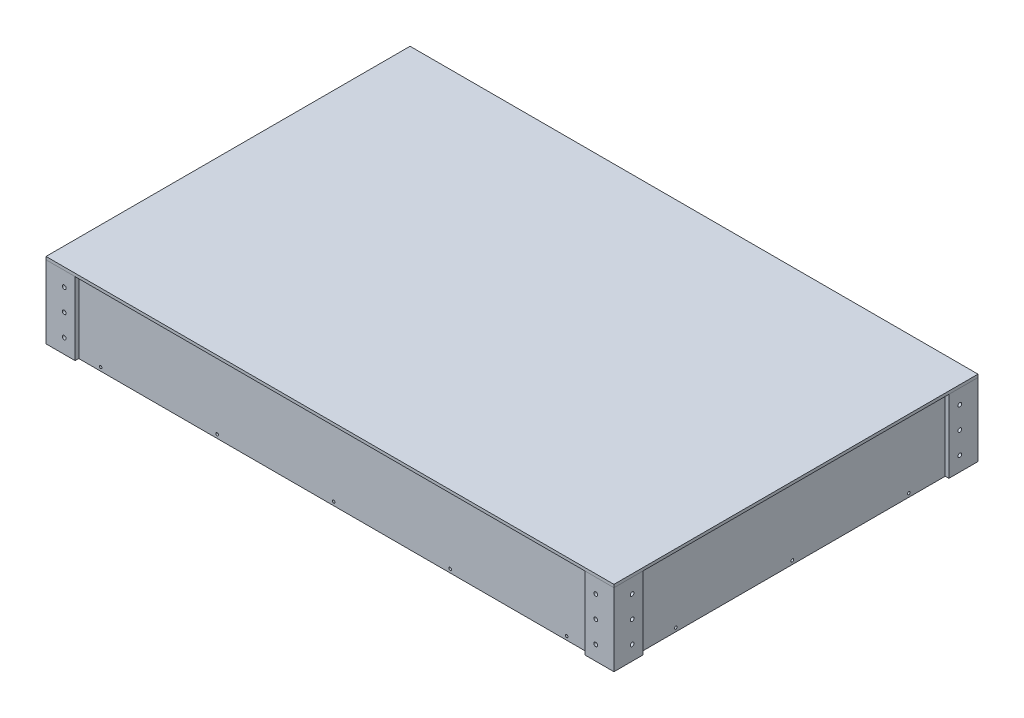
SolidWorks part; units mm, degrees
ref_plane "Front" through (0, 0, 0) normal (0, 0, 1) x (1, 0, 0)
ref_plane "Top" through (0, 0, 0) normal (0, 1, 0) x (1, 0, 0)
ref_plane "Right" through (0, 0, 0) normal (1, 0, 0) x (0, 0, -1)
sketch "Sketch1" plane through (0, 0, 0) normal (0, 1, 0) x (1, 0, 0)
  line L1 (-241.3, 152.4) -> (241.3, 152.4)
  line L2 (-241.3, 152.4) -> (-241.3, -152.4)
  line L3 (-241.3, -152.4) -> (241.3, -152.4)
  line L4 (241.3, 152.4) -> (241.3, -152.4)
  line L5 (-241.3, 152.4) -> (241.3, -152.4) construction
  line L6 (-241.3, -152.4) -> (241.3, 152.4) construction
  point P0 (0, 0)
  dimension "D1" = 482.6
  dimension "D2" = 304.8
extrude "Boss-Extrude1" add sketch "Sketch1" along normal blind 6.35
sketch "Sketch2" plane through (0, 6.35, 0) normal (0, 1, 0) x (1, 0, 0)
  line L0 (241.3, -152.4) -> (241.3, 152.4) construction
  line L1 (-241.3, 152.4) -> (241.3, 152.4)
  line L2 (-241.3, 152.4) -> (-241.3, 155.575)
  line L3 (-241.3, 155.575) -> (241.3, 155.575)
  line L4 (241.3, 152.4) -> (241.3, 155.575)
  line L5 (-241.3, 152.4) -> (241.3, 155.575) construction
  line L6 (-241.3, 155.575) -> (241.3, 152.4) construction
  line L7 (-241.3, -155.575) -> (241.3, -155.575)
  line L8 (-241.3, -155.575) -> (-241.3, -152.4)
  line L9 (-241.3, -152.4) -> (241.3, -152.4)
  line L10 (241.3, -155.575) -> (241.3, -152.4)
  line L11 (-241.3, -155.575) -> (241.3, -152.4) construction
  line L12 (-241.3, -152.4) -> (241.3, -155.575) construction
  line L13 (-241.3, 152.4) -> (-241.3, -152.4) construction
  line L14 (241.3, 152.4) -> (-241.3, 152.4) construction
  line L15 (-241.3, -152.4) -> (241.3, -152.4) construction
  point P0 (0, 153.9875)
  point P5 (0, -153.9875)
  dimension "D1" = 3.175
extrude "Boss-Extrude2" add sketch "Sketch2" along normal blind 57.15 and the other way up to surface (6.35 mm away) separate body other way up to face at (0, 0, 0)
sketch "Sketch3" plane through (0, 6.35, 0) normal (0, 1, 0) x (1, 0, 0)
  line L0 (241.3, -155.575) -> (-241.3, -155.575) construction
  line L1 (-241.3, 155.575) -> (-244.475, 155.575)
  line L2 (-241.3, 155.575) -> (-241.3, -155.575)
  line L3 (-241.3, -155.575) -> (-244.475, -155.575)
  line L4 (-244.475, 155.575) -> (-244.475, -155.575)
  line L6 (241.3, 155.575) -> (244.475, 155.575)
  line L7 (241.3, 155.575) -> (241.3, -155.575)
  line L8 (241.3, -155.575) -> (244.475, -155.575)
  line L9 (244.475, 155.575) -> (244.475, -155.575)
  dimension "D1" = 3.175
extrude "Boss-Extrude3" add sketch "Sketch3" along normal up to surface and the other way up to surface separate body
sketch "Sketch4" plane through (0, 0, 0) normal (0, -1, 0) x (1, 0, 0)
  line L0 (-244.475, -155.575) -> (-222.25, -155.575)
  line L2 (-222.25, -155.575) -> (-222.25, -158.75)
  line L3 (-222.25, -158.75) -> (-247.65, -158.75)
  line L4 (-247.65, -158.75) -> (-247.65, -133.35)
  line L5 (-247.65, -133.35) -> (-244.475, -133.35)
  line L7 (-244.475, -133.35) -> (-244.475, -155.575)
  line L8 (-244.475, 155.575) -> (-244.475, -155.575) construction
  line L9 (-241.3, -155.575) -> (241.3, -155.575) construction
  dimension "D1" = 3.175
  dimension "D2" = 25.4
  dimension "D3" = 25.4
extrude "Boss-Extrude4" add sketch "Sketch4" against normal up to surface (63.5 mm away) separate body up to face at (0, 63.5, -153.9875)
mirror "Mirror1" about plane through (0, 0, 0) normal (1, 0, 0) of bodies 184
mirror "Mirror2" about plane through (0, 0, 0) normal (0, 0, 1) of bodies 184 185
sketch "Sketch5" plane through (0, 0, -155.575) normal (0, 0, -1) x (-1, 0, 0)
  line L0 (-241.3, 31.75) -> (-222.25, 31.75) construction
  line L1 (-241.3, 0) -> (-241.3, 63.5) construction
  line L2 (-222.25, 63.5) -> (-222.25, 0) construction
  line L3 (-231.775, 50.8) -> (-231.775, 12.7) construction
  circle A0 centre (-231.775, 50.8) radius 1.651
  circle A1 centre (-231.775, 31.75) radius 1.651
  circle A2 centre (-231.775, 12.7) radius 1.651
  point P8 (-231.775, 31.75)
  dimension "D2" = 3.302
  dimension "D1" = 38.1
extrude "Cut-Extrude1" cut sketch "Sketch5" against normal through all
mirror "Mirror3" about plane through (0, 0, 0) normal (1, 0, 0) of "Cut-Extrude1"
sketch "Sketch6" plane through (-247.65, 0, 0) normal (-1, 0, 0) x (0, 0, 1)
  line L0 (-152.4, 31.75) -> (-133.35, 31.75) construction
  line L1 (-133.35, 63.5) -> (-133.35, 0) construction
  line L2 (-152.4, 0) -> (-152.4, 63.5) construction
  line L3 (-142.875, 50.8) -> (-142.875, 12.7) construction
  circle A0 centre (-142.875, 50.8) radius 1.651
  circle A1 centre (-142.875, 31.75) radius 1.651
  circle A2 centre (-142.875, 12.7) radius 1.651
  point P2 (-142.875, 31.75)
  point P5 (-142.875, 31.75)
  dimension "D2" = 3.302
  dimension "D1" = 38.1
extrude "Cut-Extrude2" cut sketch "Sketch6" against normal through all
mirror "Mirror4" about plane through (0, 0, 0) normal (0, 0, 1) of "Cut-Extrude2"
sketch "Sketch7" plane through (0, 0, 155.575) normal (0, 0, 1) x (1, 0, 0)
  line L0 (-247.65, 3.175) -> (247.65, 3.175) construction
  line L1 (-247.65, 6.35) -> (-247.65, 0) construction
  line L2 (241.3, 0) -> (-241.3, 0) construction
  line L3 (-241.3, 6.35) -> (241.3, 6.35) construction
  line L4 (247.65, 63.5) -> (247.65, 0) construction
  circle A0 centre (-203.2, 3.175) radius 1.1811
  circle A1 centre (0, 3.175) radius 1.1811
  circle A2 centre (203.2, 3.175) radius 1.1811
  circle A3 centre (101.6, 3.175) radius 1.1811
  circle A4 centre (-101.6, 3.175) radius 1.1811
  dimension "D1" = 2.3622
  dimension "D3" = 2.3622
  dimension "D4" = 101.6
  dimension "D5" = 101.6
  dimension "D6" = 203.2
  dimension "D2" = 203.2
extrude "Cut-Extrude3" cut sketch "Sketch7" against normal through all and the other way through all
sketch "Sketch8" plane through (244.475, 0, 0) normal (1, 0, 0) x (0, 0, -1)
  line L0 (-158.75, 3.175) -> (158.75, 3.175) construction
  line L1 (-158.75, 63.5) -> (-158.75, 0) construction
  line L2 (158.75, 63.5) -> (158.75, 0) construction
  line L3 (0, 0) -> (0, 6.35) construction
  line L4 (-152.4, 6.35) -> (152.4, 6.35) construction
  circle A0 centre (0, 3.175) radius 1.1811
  circle A1 centre (101.6, 3.175) radius 1.1811
  circle A2 centre (-101.6, 3.175) radius 1.1811
  point P12 (0, 3.175)
  dimension "D1" = 2.3622
  dimension "D2" = 101.6
  dimension "D3" = 101.6
extrude "Cut-Extrude4" cut sketch "Sketch8" against normal through all
sketch "Sketch9" plane through (0, 63.5, 0) normal (0, 1, 0) x (1, 0, 0)
  line L1 (247.65, -158.75) -> (-247.65, -158.75)
  line L2 (247.65, -158.75) -> (247.65, 158.75)
  line L3 (247.65, 158.75) -> (-247.65, 158.75)
  line L4 (-247.65, -158.75) -> (-247.65, 158.75)
extrude "Boss-Extrude5" add sketch "Sketch9" along normal blind 2.54 separate body
sketch "Sketch10" [suppressed] plane through (0, 66.04, 0) normal (0, 1, 0) x (1, 0, 0)
  line L0 (0, 0) -> (0, -133.35) construction
  line L1 (0, -133.35) -> (52.3875, -133.35) construction
  line L2 (0, -133.35) -> (-52.3875, -133.35) construction
  line L3 (-247.65, -158.75) -> (247.65, -158.75) construction
  circle A0 centre (52.3875, -133.35) radius 3.175
  circle A1 centre (-52.3875, -133.35) radius 3.175
  dimension "D2" = 6.35
  dimension "D1" = 104.775
  dimension "D3" = 25.4
extrude "Cut-Extrude5" [suppressed] cut sketch "Sketch10" against normal through all
sketch "Sketch11" plane through (0, 0, -155.575) normal (0, 0, -1) x (-1, 0, 0)
  line L0 (0, 0) -> (0, 57.15) construction
  line L1 (0, 57.15) -> (-215.9, 57.15) construction
  line L2 (0, 57.15) -> (215.9, 57.15) construction
  circle A0 centre (-215.9, 57.15) radius 1.651
  circle A1 centre (-107.95, 57.15) radius 1.651
  circle A2 centre (0, 57.15) radius 1.651
  circle A3 centre (107.95, 57.15) radius 1.651
  circle A4 centre (215.9, 57.15) radius 1.651
  dimension "D2" = 3.302
  dimension "D1" = 431.8
  dimension "D3" = 57.15
extrude "Cut-Extrude6" cut sketch "Sketch11" against normal up to next (3.175 mm away)
sketch "Sketch12" [suppressed] plane through (0, 66.04, 0) normal (0, 1, 0) x (1, 0, 0)
  line L0 (0, 0) -> (0, 158.75) construction
  line L1 (247.65, 158.75) -> (-247.65, 158.75) construction
  line L2 (0, 146.05) -> (-215.9, 146.05) construction
  line L3 (0, 146.05) -> (215.9, 146.05) construction
  circle A0 centre (-215.9, 146.05) radius 1.651
  circle A1 centre (0, 146.05) radius 1.651
  circle A2 centre (215.9, 146.05) radius 1.651
  circle A3 centre (107.95, 146.05) radius 1.651
  circle A4 centre (-107.95, 146.05) radius 1.651
  dimension "D2" = 3.302
  dimension "D1" = 431.8
  dimension "D3" = 12.7
extrude "Cut-Extrude7" [suppressed] cut sketch "Sketch12" against normal through all
sketch "Sketch13" plane through (0, 6.35, 0) normal (0, 1, 0) x (1, 0, 0)
  line L1 (-228.6, 127) -> (228.6, 127) construction
  line L2 (-228.6, 127) -> (-228.6, -127) construction
  line L3 (-228.6, -127) -> (228.6, -127) construction
  line L4 (228.6, 127) -> (228.6, -127) construction
  line L5 (-228.6, 127) -> (228.6, -127) construction
  line L6 (-228.6, -127) -> (228.6, 127) construction
  circle A0 centre (-228.6, 127) radius 1.651
  circle A1 centre (228.6, 127) radius 1.651
  circle A2 centre (228.6, -127) radius 1.651
  circle A3 centre (-228.6, -127) radius 1.651
  point P0 (0, 0)
  dimension "D3" = 3.302
  dimension "D1" = 457.2
  dimension "D2" = 254
extrude "Cut-Extrude8" cut sketch "Sketch13" against normal through all
sketch "Sketch14" plane through (0, 6.35, 0) normal (0, 1, 0) x (1, 0, 0)
  circle A0 centre (152.4, 127) radius 3.175 construction
  circle A1 centre (152.4, 127) radius 3.175 construction
  circle A2 centre (152.4, -127) radius 3.175 construction
  circle A3 centre (152.4, -127) radius 3.175 construction
  circle A4 centre (19.05, -127) radius 3.175 construction
  circle A5 centre (19.05, -127) radius 3.175 construction
  circle A6 centre (19.05, 127) radius 3.175 construction
  circle A7 centre (19.05, 127) radius 3.175 construction
  circle A8 centre (-114.3, 127) radius 3.175 construction
  circle A9 centre (-114.3, 127) radius 3.175 construction
  circle A10 centre (-114.3, -127) radius 3.175 construction
  circle A11 centre (-114.3, -127) radius 3.175 construction
  circle A12 centre (152.4, 127) radius 6.35
  circle A13 centre (152.4, -127) radius 6.35
  circle A14 centre (19.05, -127) radius 6.35
  circle A15 centre (19.05, 127) radius 6.35
  circle A16 centre (-114.3, 127) radius 6.35
  circle A17 centre (-114.3, -127) radius 6.35
  dimension "D1" = 12.7
extrude "Cut-Extrude9" cut sketch "Sketch14" against normal through all
